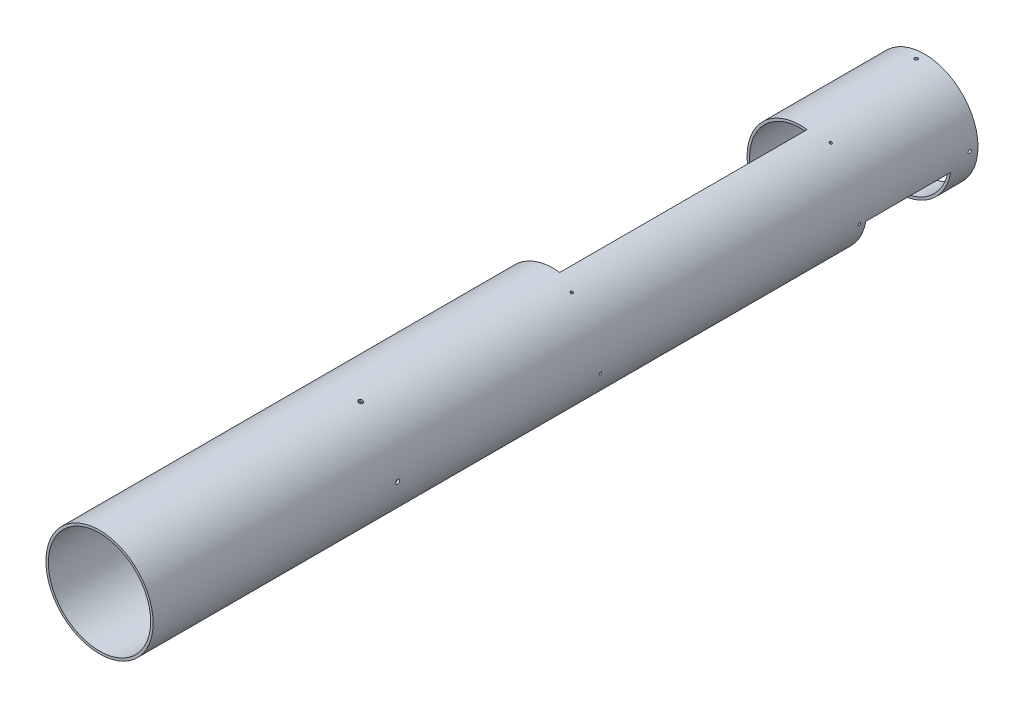
SolidWorks part; units mm, degrees
ref_plane "Front Plane" through (0, 0, 0) normal (0, 0, 1) x (1, 0, 0)
ref_plane "Top Plane" through (0, 0, 0) normal (0, 1, 0) x (1, 0, 0)
ref_plane "Right Plane" through (0, 0, 0) normal (1, 0, 0) x (0, 0, -1)
sketch "Sketch1" plane through (0, 0, 0) normal (0, 0, 1) x (1, 0, 0)
  circle A0 centre (0, 0) radius 62
  circle A1 centre (0, 0) radius 65
  dimension "D1" = 124
  dimension "D2" = 3
extrude "Boss-Extrude1" add sketch "Sketch1" along normal blind 1000
sketch "Sketch2" plane through (0, 0, 0) normal (0, 1, 0) x (1, 0, 0)
  line L0 (62, 0) -> (-62, 0) construction
  circle A0 centre (0, -224) radius 1
  circle A1 centre (0, -264) radius 1
  dimension "D1" = 2
  dimension "D3" = 2
  dimension "D2" = 224
  dimension "D4" = 40
ref_plane "Plane1" through (0, 0, 0) normal (-0.7071, 0.7071, 0) x (0.7071, 0.7071, 0)
ref_plane "Plane2" through (-28.2843, 28.2843, 0) normal (-0.7071, 0.7071, 0) x (0.7071, 0.7071, 0)
sketch "Sketch4" plane through (-28.2843, 28.2843, 0) normal (-0.7071, 0.7071, 0) x (0.7071, 0.7071, 0)
  line L0 (-65, 0) -> (-65, -1000) construction
  line L1 (-65, -150) -> (65, -150)
  line L2 (-65, -150) -> (-65, -450)
  line L3 (-65, -450) -> (65, -450)
  line L4 (65, -150) -> (65, -450)
  line L5 (65, -1000) -> (65, 0) construction
  line L6 (65, 0) -> (-65, 0) construction
  dimension "D1" = 150
  dimension "D2" = 300
extrude "Cut-Extrude4" cut sketch "Sketch4" along normal blind 516
sketch "Sketch5" plane through (0, 0, 0) normal (0, 1, 0) x (1, 0, 0)
  line L0 (-62, 0) -> (62, 0) construction
  circle A0 centre (0, -10) radius 2
  dimension "D1" = 4
  dimension "D2" = 10
extrude "Cut-Extrude5" cut sketch "Sketch5" against normal blind 85
pattern_circular "CirPattern1" count 4 every 90 about axis through (0, 0, 1000) along (0, 0, -1) of "Cut-Extrude5"
sketch "Sketch7" plane through (-28.2843, 28.2843, 0) normal (-0.7071, 0.7071, 0) x (0.7071, 0.7071, 0)
  line L0 (-51.2348, -150) -> (51.2348, -150) construction
  line L1 (47.3709, -450) -> (-47.3709, -450) construction
  circle A0 centre (0, -143) radius 1.5
  circle A1 centre (0, -457) radius 1.5
  dimension "D1" = 3
  dimension "D3" = 3
  dimension "D2" = 7
  dimension "D4" = 7
extrude "Cut-Extrude6" cut sketch "Sketch7" along normal blind 243
pattern_circular "CirPattern2" count 5 every 72 about axis through (0, 0, 1000) along (0, 0, -1) of "Cut-Extrude6"
sketch "Sketch8" plane through (0, 0, 0) normal (1, 0, 0) x (0, 0, -1)
  line L0 (-1000, 65) -> (-1000, -65) construction
  circle A0 centre (-703.5, 0) radius 2.5
  dimension "D2" = 5
  dimension "D1" = 296.5
extrude "Cut-Extrude7" cut sketch "Sketch8" along normal blind 209
pattern_circular "CirPattern3" count 5 every 72 about axis through (0, 0, 1000) along (0, 0, -1) of "Cut-Extrude7"
ref_plane "Plane3" through (0, 0, 135) normal (0, 0, 1) x (1, 0, 0)
sketch "Sketch9" plane through (0, 0, 135) normal (0, 0, 1) x (1, 0, 0)
  line L0 (-72.0694, 72.0694) -> (72.0694, -72.0694) construction
  line L2 (38.8909, 38.8909) -> (-38.8909, -38.8909) construction
  line L3 (0, 0) -> (11.2871, -64.0125)
  line L4 (1, 0) -> (-1, 0) construction
  line L5 (0, 0) -> (64.0125, -11.2871)
  arc A0 (11.2871, -64.0125) -> (64.0125, -11.2871) centre (0, 0) ccw
  point P6 (0, 0)
  dimension "D1" = 35
extrude "Cut-Extrude8" cut sketch "Sketch9" against normal blind 103
ref_plane "Plane4" through (-28.2843, 28.2843, 0) normal (-0.7071, 0.7071, 0) x (0.7071, 0.7071, 0)
sketch "Sketch11" plane through (-28.2843, 28.2843, 0) normal (-0.7071, 0.7071, 0) x (0.7071, 0.7071, 0)
  line L0 (0, 0) -> (0.045, -455.5007) construction
  circle A0 centre (0, -457) radius 1.5 construction
ref_plane "Plane5" through (0, 0, 0) normal (-0.7071, -0.7071, 0.0001) x (0.0001, 0.0001, 1)
sketch "Sketch12" plane through (0, 0, 0) normal (-0.7071, -0.7071, 0.0001) x (0.0001, 0.0001, 1)
  line L0 (150, 65) -> (458.5, 65) construction
  line L1 (304.25, 65) -> (304.25, 0)
  line L3 (304.25, 149.9397) -> (304.25, 40.3241) construction
  spline S0 degree 3 poles (184.5105, 1.378) (228.621, 23.6412) (145.9943, 11.8754) (170.9271, -12.549) (184.5105, 1.378) (228.621, 23.6412) (145.9943, 11.8754) knots -0.542614 -0.417753 -0.282999 0 0.457386 0.582247 0.717001 1 1.457386 1.582247 1.717001 only from (204.0491, 14.9821) to (204.0491, 14.9821)
  spline S1 degree 1 poles (204.0491, 14.9821) (304.25, 175.3798) knots 0 0 1 1
  spline S2 degree 3 poles (423.9895, 1.378) (379.879, 23.6412) (462.5057, 11.8754) (437.5729, -12.549) (423.9895, 1.378) (379.879, 23.6412) (462.5057, 11.8754) knots -0.542614 -0.417753 -0.282999 0 0.457386 0.582247 0.717001 1 1.457386 1.582247 1.717001 only from (404.4509, 14.9821) to (404.4509, 14.9821)
  spline S3 degree 1 poles (404.4509, 14.9821) (304.25, 175.3798) knots 0 0 1 1
  point P11 (304.25, 0)
  dimension "D1" = 65
  dimension "D2" = 100.2009
  dimension "D3" = 0
  dimension "D4" = 100.2009
ref_plane "Plane6" through (-123.991, 124.0335, 304.25) normal (0.7071, -0.7071, 0) x (-0.7071, -0.7071, 0)
sketch "Sketch15" plane through (-123.991, 124.0335, 304.25) normal (0.7071, -0.7071, 0) x (-0.7071, -0.7071, 0)
  circle A0 centre (0, 0) radius 1.5
sketch "Sketch16" plane through (-124.7077, 123.3169, -146.1261) normal (0.7071, -0.7071, 0) x (0.5, 0.5, -0.7071)
  circle A0 centre (0, 0) radius 1.5
ref_plane "Plane7" through (0, 0, 275) normal (0, 0, -1) x (-1, 0, 0)
